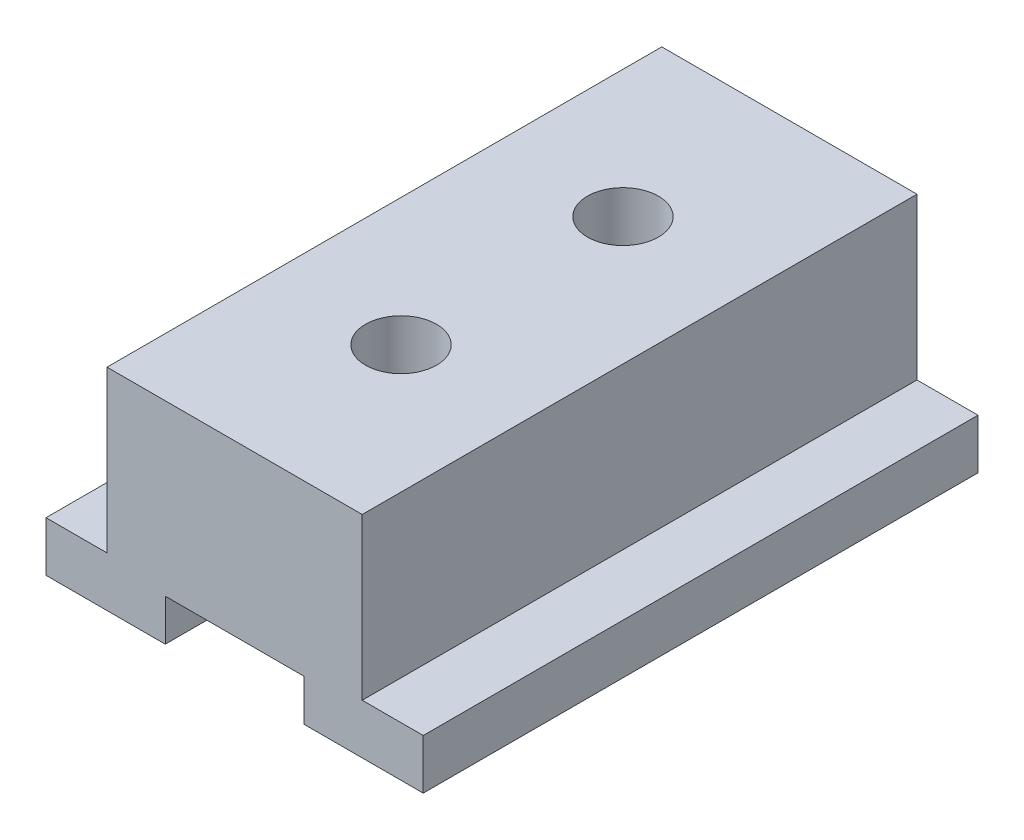
SolidWorks part; units mm, degrees
material "ABS"
ref_plane "Front Plane" through (0, 0, 0) normal (0, 0, 1) x (1, 0, 0)
ref_plane "Top Plane" through (0, 0, 0) normal (0, 1, 0) x (1, 0, 0)
ref_plane "Right Plane" through (0, 0, 0) normal (1, 0, 0) x (0, 0, -1)
sketch "Sketch1" plane through (0, 0, 0) normal (0, 0, 1) x (1, 0, 0)
  line L0 (0, 0) -> (0, 4.5)
  line L1 (0, 4.5) -> (5.5, 4.5)
  line L2 (5.5, 4.5) -> (5.5, 19)
  line L3 (5.5, 19) -> (28.5, 19)
  line L4 (28.5, 19) -> (28.5, 4.5)
  line L5 (28.5, 4.5) -> (34, 4.5)
  line L6 (34, 4.5) -> (34, 0)
  line L7 (10.75, 3.75) -> (23.25, 3.75)
  line L11 (23.25, 3.75) -> (23.25, 0)
  line L12 (34, 0) -> (23.25, 0)
  line L14 (10.75, 3.75) -> (10.75, 0)
  line L15 (10.75, 0) -> (0, 0)
  dimension "D1" = 4.5
  dimension "D2" = 3.75
  dimension "D3" = 10.75
  dimension "D4" = 5.5
  dimension "D5" = 12.5
  dimension "D6" = 10.75
  dimension "D7" = 19
  dimension "D8" = 5.5
  dimension "D9" = 4.5
extrude "Boss-Extrude1" add sketch "Sketch1" along normal blind 50
hole_wizard "M6 Clearance Hole1" positions "3DSketch1" profile "Sketch5" hole size "M6" standard "Ansi Metric" end condition through all
sketch3d "3DSketch1"
  line L2 (28.5, 19, 25) -> (5.5, 19, 25) construction
  line L3 (28.5, 19, 50) -> (28.5, 19, 0) construction
  line L4 (5.5, 19, 50) -> (5.5, 19, 0) construction
  line L6 (17, 19, 50) -> (17, 19, 0) construction
  line L7 (28.5, 19, 50) -> (5.5, 19, 50) construction
  line L8 (28.5, 19, 0) -> (5.5, 19, 0) construction
  point P0 (17, 19, 15)
  point P4 (17, 19, 35)
  dimension "D1" = 10
  dimension "D2" = 10
sketch "Sketch5" plane through (17, 19, 15) normal (1, 0, 0) x (0, 0, 1)
  line L0 (0, 0) -> (0, 19)
  line L1 (0, 19) -> (3.2, 19)
  line L2 (3.2, 19) -> (3.2, 0)
  line L5 (3.2, 0) -> (0, 0)
  line L11 (0, -6.35) -> (0, 107.95) construction
  dimension "Thru Hole Dia." = 6.4
  dimension "Thru Hole Depth" = 19
